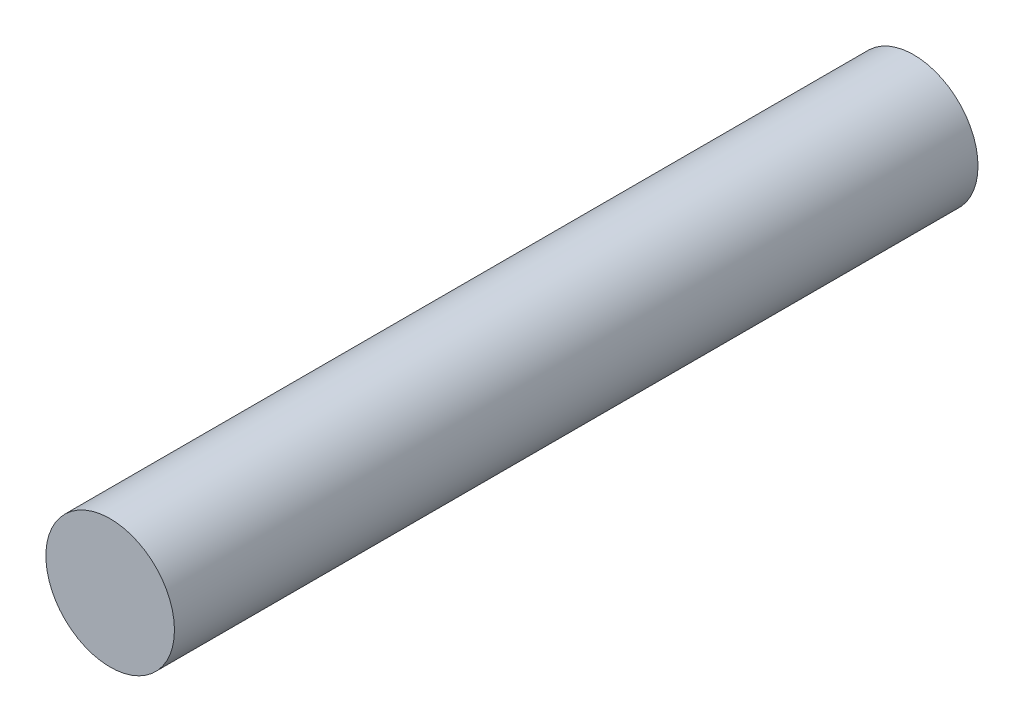
SolidWorks part; units mm, degrees
ref_plane "前视基准面" through (0, 0, 0) normal (0, 0, 1) x (1, 0, 0)
ref_plane "上视基准面" through (0, 0, 0) normal (0, 1, 0) x (1, 0, 0)
ref_plane "右视基准面" through (0, 0, 0) normal (1, 0, 0) x (0, 0, -1)
sketch "草图1" plane through (0, 0, 0) normal (0, 0, 1) x (1, 0, 0)
  circle A0 centre (0, 0) radius 4
  dimension "D1" = 8
extrude "凸台-拉伸1" add sketch "草图1" along normal blind 15
sketch "草图2" plane through (0, 0, 0) normal (0, 0, 1) x (1, 0, 0)
  circle A0 centre (0, 0) radius 4
  dimension "D1" = 8
extrude "凸台-拉伸2" add sketch "草图2" along normal blind 50
sketch "草图3" [suppressed] plane through (0, 0, 0) normal (0, 0, 1) x (1, 0, 0)
  circle A0 centre (0, 0) radius 4
  dimension "D1" = 8
sketch "草图4" plane through (0, 0, 0) normal (0, 0, 1) x (1, 0, 0)
  circle A0 centre (0, 0) radius 4
  dimension "D1" = 8
extrude "凸台-拉伸3" add sketch "草图4" along normal blind 20
